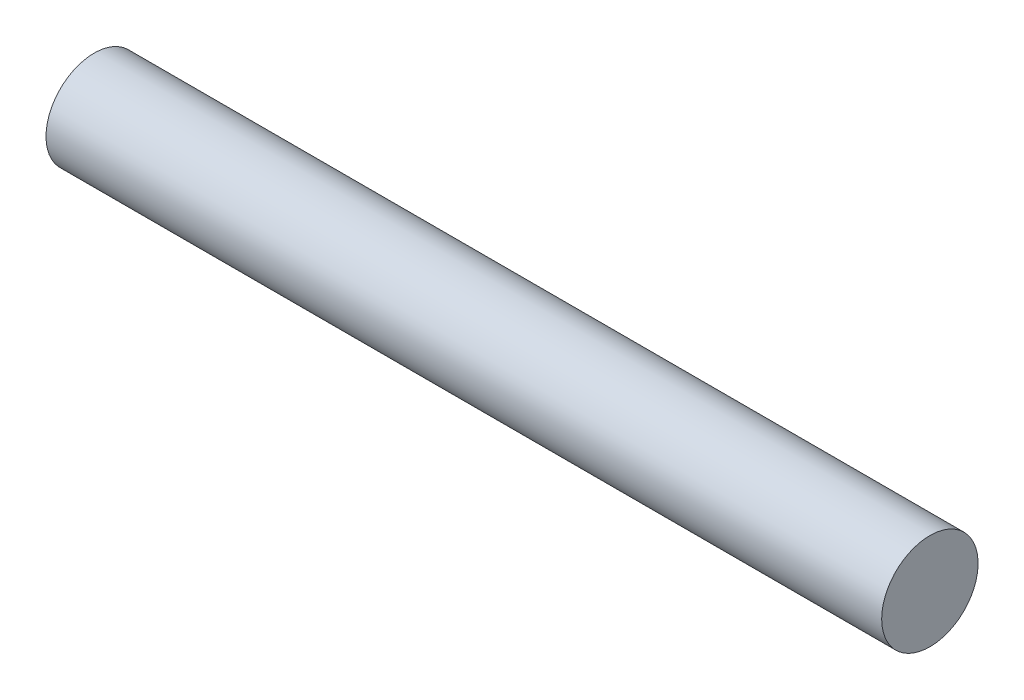
SolidWorks part; units mm, degrees
material "Brass"
ref_plane "Front Plane" through (0, 0, 0) normal (0, 0, 1) x (1, 0, 0)
ref_plane "Top Plane" through (0, 0, 0) normal (0, 1, 0) x (1, 0, 0)
ref_plane "Right Plane" through (0, 0, 0) normal (1, 0, 0) x (0, 0, -1)
sketch "Sketch2" plane through (0, 0, 0) normal (0, 0, 1) x (1, 0, 0)
  line L1 (-13, -0.75) -> (13, -0.75)
  line L2 (-13, -0.75) -> (-13, 0.75)
  line L3 (-13, 0.75) -> (13, 0.75)
  line L4 (13, -0.75) -> (13, 0.75)
  line L5 (-13, -0.75) -> (13, 0.75) construction
  line L6 (-13, 0.75) -> (13, -0.75) construction
  point P0 (0, 0)
  dimension "D1" = 26
  dimension "D2" = 1.5
revolve "Revolve2" add sketch "Sketch2" angle 360 about L1
